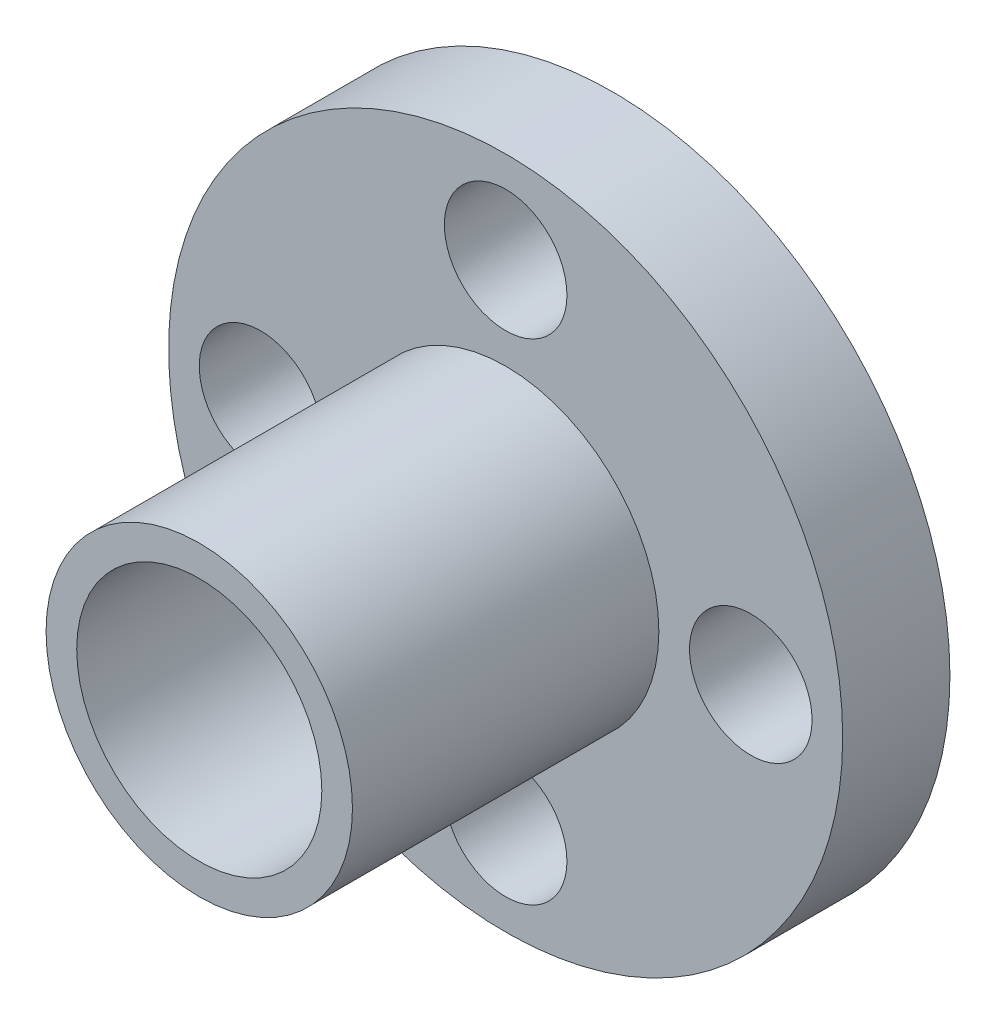
SolidWorks part; units mm, degrees
ref_plane "Plan de face" through (0, 0, 0) normal (0, 0, 1) x (1, 0, 0)
ref_plane "Plan de dessus" through (0, 0, 0) normal (0, 1, 0) x (1, 0, 0)
ref_plane "Plan de droite" through (0, 0, 0) normal (1, 0, 0) x (0, 0, -1)
sketch "Esquisse1" plane through (0, 0, 0) normal (0, 0, 1) x (1, 0, 0)
  circle A0 centre (0, 0) radius 5
  circle A1 centre (0, 0) radius 4
  dimension "D1" = 10
  dimension "D2" = 8
extrude "Boss.-Extru.1" add sketch "Esquisse1" along normal blind 15
sketch "Esquisse2" plane through (0, 0, 0) normal (0, 0, 1) x (1, 0, 0)
  circle A0 centre (0, 0) radius 11
  circle A1 centre (0, 0) radius 5 construction
  circle A2 centre (0, 0) radius 5
  dimension "D1" = 22
extrude "Boss.-Extru.2" add sketch "Esquisse2" along normal blind 3.5 from offset 1.5
sketch "Esquisse3" plane through (0, 0, 0) normal (0, 0, 1) x (1, 0, 0)
  line L0 (0, 8) -> (0, 5) construction
  line L1 (0, 8) -> (0, 11) construction
  circle A0 centre (0, 8) radius 2
  circle A1 centre (0, 0) radius 5 construction
  circle A2 centre (0, 0) radius 11 construction
  dimension "D1" = 4
extrude "Enlèv. mat.-Extru.1" cut sketch "Esquisse3" along normal through all
pattern_circular "Répétition circulaire1" count 4 over 360 about axis through (0, 0, 0) along (0, 0, 1) of "Enlèv. mat.-Extru.1"
